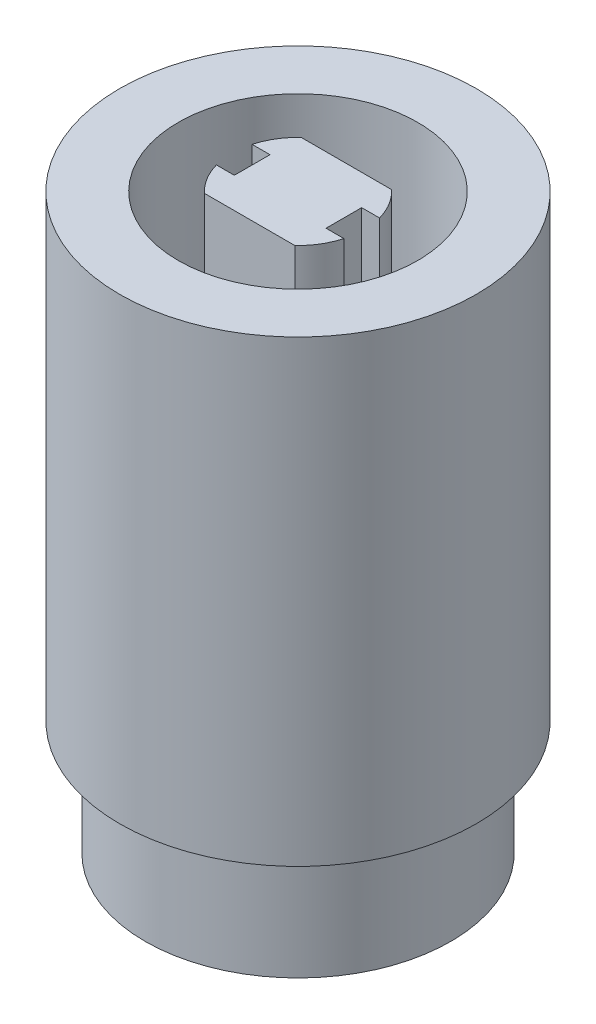
SolidWorks part; units mm, degrees
ref_plane "Alzado" through (0, 0, 0) normal (0, 0, 1) x (1, 0, 0)
ref_plane "Planta" through (0, 0, 0) normal (0, 1, 0) x (1, 0, 0)
ref_plane "Vista lateral" through (0, 0, 0) normal (1, 0, 0) x (0, 0, -1)
sketch "Croquis1" plane through (0, 0, 0) normal (0, 1, 0) x (1, 0, 0)
  circle A0 centre (0, 0) radius 6
  dimension "D1" = 12
extrude "Saliente-Extruir1" add sketch "Croquis1" along normal blind 16.5
sketch "Croquis2" plane through (0, 0, 0) normal (0, -1, 0) x (1, 0, 0)
  circle A0 centre (0, 0) radius 4.2
  dimension "D1" = 8.4
extrude "Cortar-Extruir1" cut sketch "Croquis2" against normal blind 14.5
sketch "Croquis3" plane through (0, 16.5, 0) normal (0, 1, 0) x (1, 0, 0)
  circle A0 centre (0, 0) radius 2.6
  dimension "D1" = 5.2
extrude "Saliente-Extruir2" add sketch "Croquis3" along normal blind 6
sketch "Croquis7" plane through (0, 22.5, 0) normal (0, 1, 0) x (1, 0, 0)
  line L1 (-1.7748, -1.9) -> (1.7748, -1.9)
  line L3 (-1.7748, 1.9) -> (1.7748, 1.9)
  line L5 (-2.6, -1.9) -> (2.6, 1.9) construction
  line L6 (-2.6, 1.9) -> (2.6, -1.9) construction
  arc A0 (1.7748, 1.9) -> (-1.7748, 1.9) centre (0, 0) ccw
  arc A1 (-1.7748, -1.9) -> (1.7748, -1.9) centre (0, 0) ccw
  point P0 (0, 0)
  dimension "D1" = 5.2
  dimension "D2" = 5.2
  dimension "D5" = 2.6
  dimension "D3" = 3.8
  dimension "D4" = 3.5496
  dimension "D6" = 1.7748
extrude "Cortar-Extruir4" cut sketch "Croquis7" against normal blind 6
sketch "Croquis8" plane through (0, 0, 0) normal (0, 0, 1) x (1, 0, 0)
  line L0 (0, 0) -> (0, 22.5) construction
  line L1 (1.7748, 22.5) -> (-1.7748, 22.5) construction
  line L2 (-6, 0) -> (6, 0) construction
  circle A0 centre (0, 10) radius 1.4
  dimension "D1" = 2.8
  dimension "D2" = 10
sketch "Croquis10" plane through (0, 22.5, 0) normal (0, 1, 0) x (1, 0, 0)
  line L0 (-1.8, 0.7) -> (-2.504, 0.7)
  line L1 (2.504, 0.7) -> (1.8, 0.7)
  line L3 (2.504, -0.7) -> (1.8, -0.7)
  line L5 (2.511, 0.6745) -> (-2.511, -0.6745) construction
  line L6 (2.511, -0.6745) -> (-2.511, 0.6745) construction
  line L8 (1.8, -0.7) -> (1.8, 0.7)
  line L10 (-1.8, -0.7) -> (-1.8, 0.7)
  line L11 (1.8, -0.7) -> (-1.8, 0.7) construction
  line L12 (1.8, 0.7) -> (-1.8, -0.7) construction
  line L13 (-1.8, -0.7) -> (-2.504, -0.7)
  arc A0 (-2.504, 0.7) -> (-2.504, -0.7) centre (0, 0) ccw
  arc A1 (2.504, -0.7) -> (2.504, 0.7) centre (0, 0) ccw
  dimension "D1" = 5.2
  dimension "D2" = 1.4
  dimension "D3" = 3.6
extrude "Cortar-Extruir5" cut sketch "Croquis10" against normal up to surface (6 mm away) up to face at (0, 16.5, 0)
extrude "Cortar-Extruir6" [suppressed] cut sketch "Croquis8" against normal blind 10
sketch "Croquis11" [suppressed] plane through (0, 22.5, 0) normal (0, 1, 0) x (1, 0, 0)
  line L1 (-1.8269, 1.85) -> (1.8269, 1.85)
  line L3 (-1.8269, -1.85) -> (1.8269, -1.85)
  line L5 (-2.6, 1.85) -> (2.6, -1.85) construction
  line L6 (-2.6, -1.85) -> (2.6, 1.85) construction
  arc A0 (1.8269, 1.85) -> (-1.8269, 1.85) centre (0, 0) ccw
  arc A1 (-1.8269, -1.85) -> (1.8269, -1.85) centre (0, 0) ccw
  dimension "D1" = 5.2
  dimension "D2" = 5.2
  dimension "D3" = 3.7
  dimension "D4" = 3.6538
  dimension "D5" = 1.85
extrude "Cortar-Extruir7" [suppressed] cut sketch "Croquis11" against normal up to surface (6 mm away)
sketch "Croquis12" [suppressed] plane through (0, 22.5, 0) normal (0, 1, 0) x (1, 0, 0)
  line L1 (1.8762, -1.8) -> (-1.8762, -1.8)
  line L3 (1.8762, 1.8) -> (-1.8762, 1.8)
  line L5 (2.6, -1.8) -> (-2.6, 1.8) construction
  line L6 (2.6, 1.8) -> (-2.6, -1.8) construction
  arc A0 (-1.8762, -1.8) -> (1.8762, -1.8) centre (0, 0) ccw
  arc A1 (1.8762, 1.8) -> (-1.8762, 1.8) centre (0, 0) ccw
  arc A2 (-2.504, -0.7) -> (-1.7748, -1.9) centre (0, 0) ccw construction
  dimension "D1" = 5.2
  dimension "D2" = 5.2
  dimension "D3" = 3.6
  dimension "D4" = 3.7523
  dimension "D5" = 1.8
extrude "Cortar-Extruir8" [suppressed] cut sketch "Croquis12" against normal up to surface (6 mm away)
sketch "Croquis13" plane through (0, 16.5, 0) normal (0, 1, 0) x (1, 0, 0)
  circle A0 centre (0, 0) radius 4.7
  circle A1 centre (0, 0) radius 7
  dimension "D1" = 9.4
  dimension "D2" = 14
extrude "Saliente-Extruir3" add sketch "Croquis13" along normal blind 6 and the other way blind 12
sketch "Croquis14" plane through (0, 0, 0) normal (0, 0, 1) x (1, 0, 0)
  line L0 (0, 0) -> (0, 22.5) construction
  line L1 (-1.7748, 22.5) -> (1.7748, 22.5) construction
  line L2 (-6, 0) -> (6, 0) construction
  circle A0 centre (0, 10) radius 1.4
  dimension "D1" = 2.8
  dimension "D2" = 10
extrude "Cortar-Extruir9" cut sketch "Croquis14" against normal up to next
